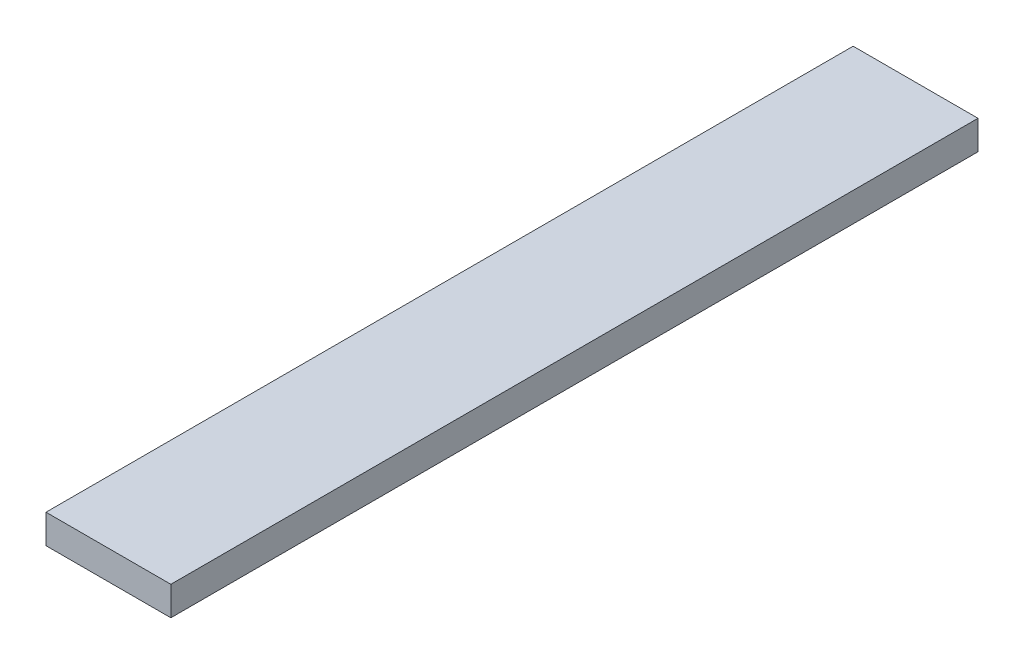
SolidWorks part; units mm, degrees
material "Mahogany"
ref_plane "Front Plane" through (0, 0, 0) normal (0, 0, 1) x (1, 0, 0)
ref_plane "Top Plane" through (0, 0, 0) normal (0, 1, 0) x (1, 0, 0)
ref_plane "Right Plane" through (0, 0, 0) normal (1, 0, 0) x (0, 0, -1)
sketch "Base_Sketch" plane through (0, 0, 0) normal (0, 1, 0) x (1, 0, 0)
  line L0 (-25.4, 0) -> (25.4, 0) construction
  line L1 (-25.4, 164.21) -> (25.4, 164.21)
  line L2 (-25.4, 164.21) -> (-25.4, -164.21)
  line L3 (-25.4, -164.21) -> (25.4, -164.21)
  line L4 (25.4, 164.21) -> (25.4, -164.21)
  line L5 (-25.4, 164.21) -> (25.4, -164.21) construction
  line L6 (-25.4, -164.21) -> (25.4, 164.21) construction
  line L7 (-13.59, -152.4) -> (13.59, -152.4) construction
  line L8 (13.59, 152.4) -> (13.59, -152.4) construction
  line L9 (-13.59, 152.4) -> (13.59, 152.4) construction
  line L10 (-13.59, 152.4) -> (-13.59, -152.4) construction
  line L11 (-37.21, -176.02) -> (37.21, -176.02) construction
  line L12 (37.21, 176.02) -> (37.21, -176.02) construction
  line L13 (-37.21, 176.02) -> (37.21, 176.02) construction
  line L14 (-37.21, 176.02) -> (-37.21, -176.02) construction
  line L16 (59.2667, -152.4) -> (33.8667, -152.4) construction
  point P0 (0, 0)
  dimension "D1" = 50.8
  dimension "D2" = 11.81
  dimension "D3" = 11.81
extrude "Boss-Extrude1" add sketch "Base_Sketch" along normal blind 11.81
equation "\"Material_Thickness\"= \"Material_Thickness@Petrov.Assembly\""
equation "\"D1@Boss-Extrude1\"=\"Material_Thickness\""
equation "\"Width\"= \"Accent_Width@Petrov.Assembly\""
equation "\"D1@Base_Sketch\"=\"Width\""
equation "\"D2@Base_Sketch\"=\"Material_Thickness\""
equation "\"D3@Base_Sketch\"=\"Material_Thickness\""
